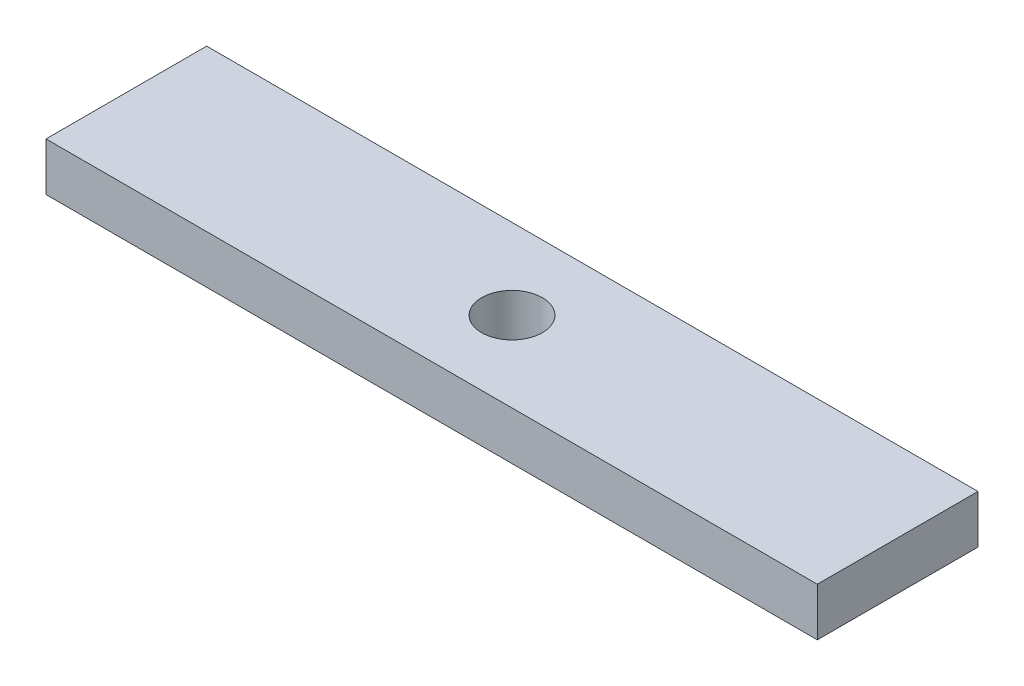
SolidWorks part; units mm, degrees
ref_plane "Front Plane" through (0, 0, 0) normal (0, 0, 1) x (1, 0, 0)
ref_plane "Top Plane" through (0, 0, 0) normal (0, 1, 0) x (1, 0, 0)
ref_plane "Right Plane" through (0, 0, 0) normal (1, 0, 0) x (0, 0, -1)
sketch "Sketch1" plane through (0, 0, 0) normal (0, 1, 0) x (1, 0, 0)
  line L1 (-76.2, -15.875) -> (76.2, -15.875)
  line L2 (-76.2, -15.875) -> (-76.2, 15.875)
  line L3 (-76.2, 15.875) -> (76.2, 15.875)
  line L4 (76.2, -15.875) -> (76.2, 15.875)
  line L5 (-76.2, -15.875) -> (76.2, 15.875) construction
  line L6 (-76.2, 15.875) -> (76.2, -15.875) construction
  point P0 (0, 0)
  dimension "D1" = 152.4
  dimension "D2" = 31.75
extrude "Boss-Extrude1" add sketch "Sketch1" along normal mid plane 9.525
sketch "Sketch3" [suppressed] plane through (0, 4.7625, 0) normal (0, 1, 0) x (1, 0, 0)
  point P0 (-71.4375, 9.525)
  point P1 (-71.4375, -9.525)
hole_wizard "CSK for M3 Flat Head Machine Screw1" [suppressed] positions "Sketch4" profile "Sketch6" countersink size "M3" standard "ANSI Metric"
sketch "Sketch4" [suppressed] plane through (0, 4.7625, 0) normal (0, 1, 0) x (1, 0, 0)
  point P0 (-71.4375, 9.525)
  point P3 (-71.4375, -9.525)
sketch "Sketch6" plane through (-71.4375, 4.7625, -9.525) normal (1, 0, 0) x (0, 0, 1)
  line L0 (0, 0) -> (0, 13.6614)
  line L1 (0, 13.6614) -> (1.6, 12.7)
  line L2 (1.6, 12.7) -> (1.6, 1.55)
  line L3 (1.6, 1.55) -> (3.15, 0)
  line L5 (3.15, 0) -> (0, 0)
  line L6 (-1.6, 1.55) -> (-3.15, 0) construction
  line L10 (0, 13.6614) -> (-1.6, 12.7) construction
  line L11 (0, -6.35) -> (0, 107.95) construction
  dimension "Hole Dia." = 3.2
  dimension "Hole Depth" = 12.7
  dimension "Near C'Sink Dia." = 6.3
  dimension "Near C'Sink Angle" = 90
  dimension "Drill Angle" = 118
mirror "Mirror1" [suppressed] about plane through (0, 0, 0) normal (1, 0, 0)
sketch "Sketch7" plane through (0, -4.7625, 0) normal (0, -1, 0) x (1, 0, 0)
  point P0 (0, 0)
hole_wizard "Ø12.0mm Dowel Hole1" positions "Sketch8" profile "Sketch9" hole size "Ø12.0" standard "ANSI Metric" end condition through all
sketch "Sketch8" plane through (0, -4.7625, 0) normal (0, -1, 0) x (-1, 0, 0)
  point P0 (0, 0)
sketch "Sketch9" plane through (0, -4.7625, 0) normal (1, 0, 0) x (0, 0, -1)
  line L0 (0, 0) -> (0, 9.525)
  line L1 (0, 9.525) -> (6, 9.525)
  line L2 (6, 9.525) -> (6, 0)
  line L5 (6, 0) -> (0, 0)
  line L11 (0, -6.35) -> (0, 107.95) construction
  dimension "Thru Hole Dia." = 12
  dimension "Thru Hole Depth" = 9.525
